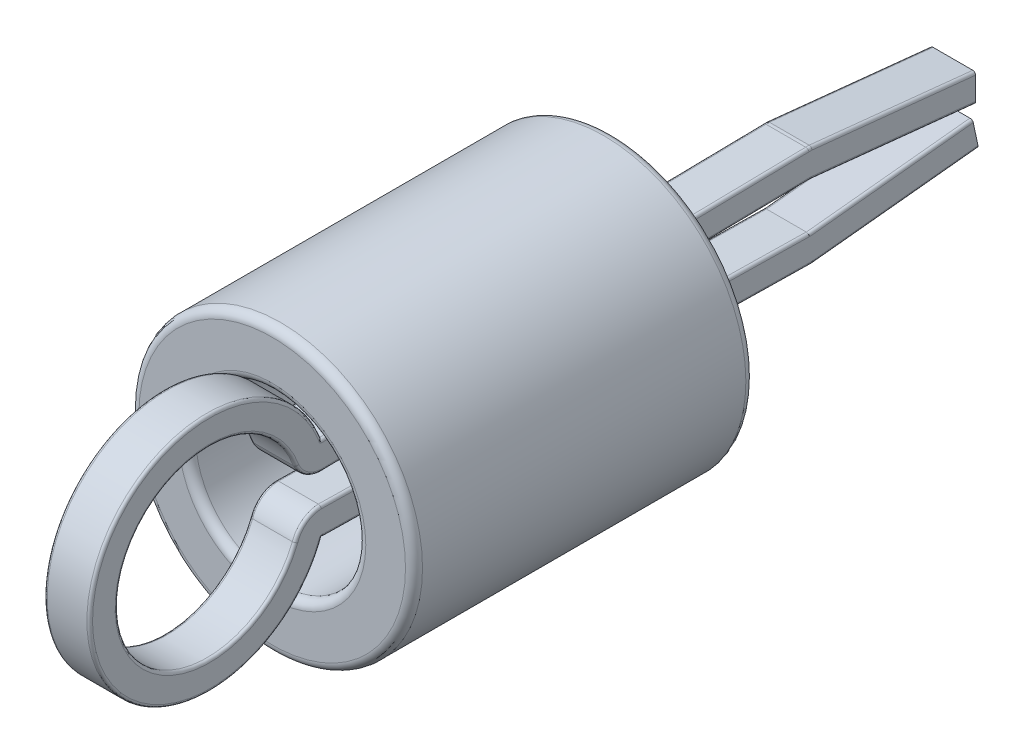
SolidWorks part; units mm, degrees
ref_plane "Front Plane" through (0, 0, 0) normal (0, 0, 1) x (1, 0, 0)
ref_plane "Top Plane" through (0, 0, 0) normal (0, 1, 0) x (1, 0, 0)
ref_plane "Right Plane" through (0, 0, 0) normal (1, 0, 0) x (0, 0, -1)
sketch "Sketch1" plane through (0, 0, 0) normal (0, 0, 1) x (1, 0, 0)
  circle A0 centre (0, 0) radius 1.27
  circle A1 centre (0, 0) radius 0.762
  dimension "D1" = 2.54
  dimension "D2" = 0.508
extrude "Plastic-Ring" add sketch "Sketch1" along normal blind 3.048
fillet "Fillet1" radius 0.0762 4 edges at (0.762, 0, 0) (1.27, 0, 0) (0.762, 0, 3.048) (1.27, 0, 3.048)
sketch "wire-bend" plane through (0, 0, 0) normal (1, 0, 0) x (0, 0, -1)
  line L0 (-5.3581, 0) -> (4.6063, 0) construction
  line L1 (1.5672, -0.3301) -> (-2.8021, -0.2556)
  line L2 (3.048, 0.1778) -> (1.5824, 0.3294)
  line L4 (1.5672, 0.3301) -> (-2.8021, 0.2556)
  line L7 (3.048, -0.1778) -> (1.5824, -0.3294)
  arc A0 (-2.923, 0.3374) -> (-2.923, -0.3374) centre (-3.81, 0) ccw
  arc A1 (-2.8021, 0.2556) -> (-2.923, 0.3374) centre (-2.8043, 0.3826) cw
  arc A2 (1.5824, 0.3294) -> (1.5672, 0.3301) centre (1.5693, 0.2031) ccw
  arc A3 (1.5824, -0.3294) -> (1.5672, -0.3301) centre (1.5693, -0.2031) cw
  arc A4 (-2.8021, -0.2556) -> (-2.923, -0.3374) centre (-2.8043, -0.3826) ccw
  point P12 (-2.8956, 0.254)
  point P15 (1.5748, 0.3302)
  point P23 (1.5748, -0.3302)
  point P24 (-2.8956, -0.254)
  dimension "D2" = 0.127
  dimension "D1" = 3.81
  dimension "D3" = 0.1778
  dimension "D4" = 3.048
  dimension "D5" = 1.5748
  dimension "D6" = 0.3302
  dimension "D7" = 0.254
  dimension "D8" = 2.8956
ref_plane "Plane1" through (0, 0, -3.048) normal (0, 0, 1) x (1, 0, 0)
sketch "wire-profile" plane through (0, 0, -3.048) normal (0, 0, 1) x (1, 0, 0)
  line L1 (-0.1778, 0.3048) -> (0.1778, 0.3048)
  line L2 (-0.2032, 0.2794) -> (-0.2032, 0.0762)
  line L3 (-0.1778, 0.0508) -> (0.1778, 0.0508)
  line L4 (0.2032, 0.2794) -> (0.2032, 0.0762)
  line L5 (-0.2032, 0.3048) -> (0.2032, 0.0508) construction
  line L6 (-0.2032, 0.0508) -> (0.2032, 0.3048) construction
  arc A0 (0.1778, 0.3048) -> (0.2032, 0.2794) centre (0.1778, 0.2794) cw
  arc A1 (0.1778, 0.0508) -> (0.2032, 0.0762) centre (0.1778, 0.0762) ccw
  arc A2 (-0.2032, 0.0762) -> (-0.1778, 0.0508) centre (-0.1778, 0.0762) ccw
  arc A3 (-0.1778, 0.3048) -> (-0.2032, 0.2794) centre (-0.1778, 0.2794) ccw
  point P0 (0, 0.1778)
  dimension "D3" = 0.0254
  dimension "D1" = 0.254
  dimension "D2" = 0.4064
sweep "Sweep3" add profiles "wire-profile" path "wire-bend"
ref_plane "Plane2" through (0, 0, -1.5748) normal (0, 0, 1) x (1, 0, 0)
sketch "VIA hole" plane through (0, 0, -1.5748) normal (0, 0, 1) x (1, 0, 0)
  circle A0 centre (0, 0) radius 0.508 construction
  circle A1 centre (0, 0) radius 0.5334 construction
  dimension "D1" = 1.016
  dimension "D2" = 0.0254
